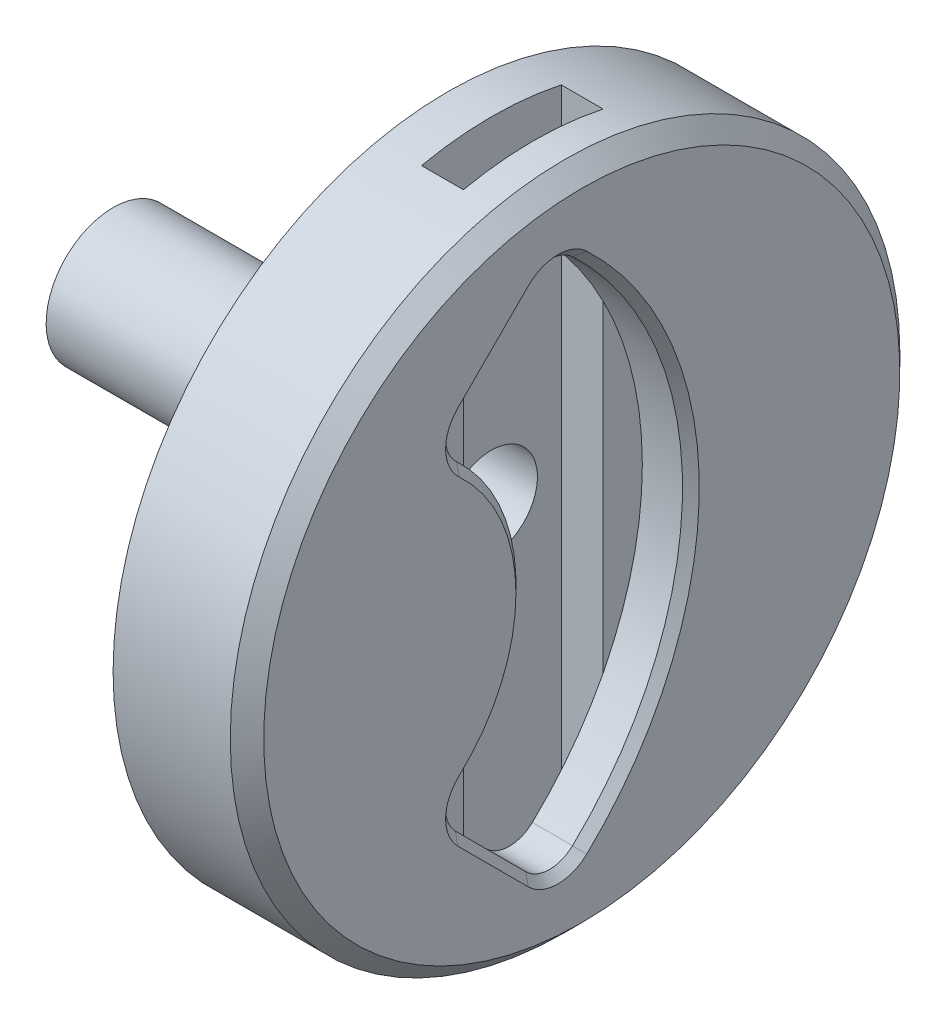
SolidWorks part; units mm, degrees
ref_plane "Alzado" through (0, 0, 0) normal (0, 0, 1) x (1, 0, 0)
ref_plane "Planta" through (0, 0, 0) normal (0, 1, 0) x (1, 0, 0)
ref_plane "Vista lateral" through (0, 0, 0) normal (1, 0, 0) x (0, 0, -1)
sketch "Croquis1" plane through (0, 0, 0) normal (0, 0, 1) x (1, 0, 0)
  line L0 (-20, 0) -> (-20, 4)
  line L1 (-20, 4) -> (0, 4)
  line L2 (0, 4) -> (0, 20)
  line L3 (0, 20) -> (8, 20)
  line L4 (8, 20) -> (8, 0)
  line L5 (8, 0) -> (-20, 0) construction
  line L6 (-20, 0) -> (8, 0)
  dimension "D1" = 40
  dimension "D2" = 8
  dimension "D3" = 20
  dimension "D4" = 8
revolve "Revolución1" add sketch "Croquis1" angle 360 about L5
sketch "Croquis2" plane through (8, 0, 0) normal (1, 0, 0) x (0, 0, -1)
  line L0 (0, 20) -> (0, -20) construction
  line L1 (-18.0333, 0) -> (-7.049, 10.9843) construction
  line L2 (-18.0333, 0) -> (-7.049, -10.9843) construction
  line L3 (-2.8392, 15.1941) -> (-7.049, 10.9843)
  line L4 (-7.049, -10.9843) -> (-2.8392, -15.1941)
  line L5 (-14.4333, 0) -> (-18.0333, 0) construction
  line L6 (-1.4538, 15.7797) -> (7.1943, 15.7797) construction
  line L7 (-1.4538, -15.7797) -> (8.9899, -15.7797) construction
  circle A0 centre (0, 0) radius 20 construction
  arc A1 (-0.0521, 15.2342) -> (-0.0521, -15.2342) centre (-14.4333, 0) cw
  arc A2 (-6.9884, 8.0978) -> (-6.9884, -8.0978) centre (-14.4333, 0) cw
  arc A3 (-0.0521, -15.2342) -> (-2.8392, -15.1941) centre (-1.425, -13.7799) cw
  arc A4 (-6.9884, -8.0978) -> (-7.049, -10.9843) centre (-5.6348, -9.5701) ccw
  arc A5 (-6.9884, 8.0978) -> (-7.049, 10.9843) centre (-5.6348, 9.5701) cw
  arc A6 (-0.0521, 15.2342) -> (-2.8392, 15.1941) centre (-1.425, 13.7799) ccw
  point P24 (-3.4333, 0)
  dimension "D1" = 20.95
  dimension "D2" = 11
  dimension "D4" = 2
  dimension "D3" = 90
  dimension "D5" = 3.6
extrude "Cortar-Extruir1" cut sketch "Croquis2" against normal blind 2.9
fillet "Redondeo1" radius 10 1 edges at (0, 4, 0)
sketch "Croquis3" plane through (-20, 0, 0) normal (-1, 0, 0) x (0, 0, 1)
  circle A0 centre (0, 0) radius 1.75
  dimension "D1" = 3.5
extrude "Cortar-Extruir2" cut sketch "Croquis3" against normal up to next
sketch "Croquis4" plane through (5.1, 0, 0) normal (1, 0, 0) x (0, 0, -1)
  circle A0 centre (0, 0) radius 2.75
  dimension "D1" = 5.5
extrude "Cortar-Extruir3" cut sketch "Croquis4" against normal offset from surface (22.1 mm away) 3 up to face at (-20, -1.75, 0)
chamfer "Chaflán1" distance 1 angle 45 1 edges at (8, 20, 0)
chamfer "Chaflán2" distance 0.5 angle 45 8 edges at (8, 0, 3.4333) (8, -9.5281, 7.6344) (8, 9.5281, 7.6344) (8, -13.0892, 4.9441) (8, 13.0892, 4.9441) (8, -15.7797, 1.4538) (8, 15.7797, 1.4538) (8, 0, -6.5167)
sketch "Croquis5" plane through (8, 0, 0) normal (1, 0, 0) x (0, 0, -1)
  circle A0 centre (0, 0) radius 13.05
  dimension "D1" = 26.1
sketch "Croquis6" plane through (0, 0, 0) normal (0, 1, 0) x (1, 0, 0)
  line L0 (2.6, 4.175) -> (2.6, -4.175)
  line L1 (2.6, -4.175) -> (5.1, -4.175)
  line L2 (5.1, -4.175) -> (5.1, 4.175)
  line L7 (5.1, 4.175) -> (2.6, 4.175)
  line L8 (5.1, -2.75) -> (5.1, 2.75) construction
  line L9 (-15.4, 0) -> (15.4, 0) construction
  point P2 (0, 0)
  point P5 (-0.2368, -2.4743)
  point P6 (-0.4486, 2.3385)
  point P8 (5.1, 0)
  dimension "D1" = 8.35
  dimension "D3" = 2.5
extrude "Cortar-Extruir5" cut sketch "Croquis6" against normal mid plane 50
